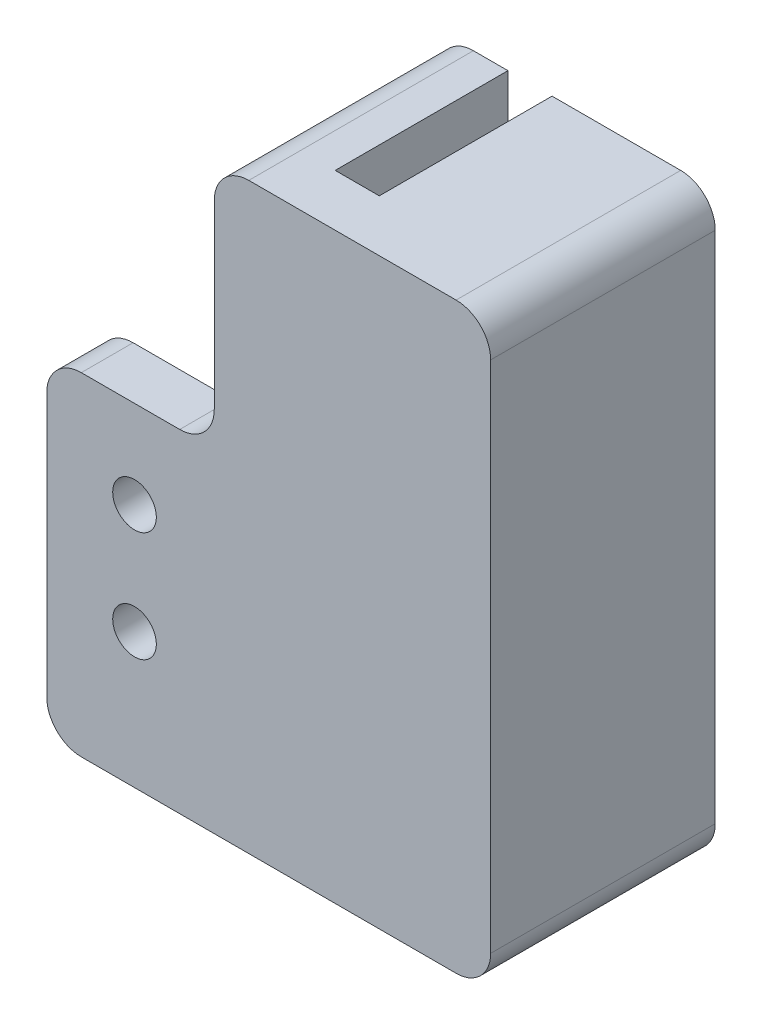
SolidWorks part; units mm, degrees
ref_plane "Front Plane" through (0, 0, 0) normal (0, 0, 1) x (1, 0, 0)
ref_plane "Top Plane" through (0, 0, 0) normal (0, 1, 0) x (1, 0, 0)
ref_plane "Right Plane" through (0, 0, 0) normal (1, 0, 0) x (0, 0, -1)
sketch "Sketch1" plane through (0, 0, 0) normal (0, 0, 1) x (1, 0, 0)
  line L16 (520, -4) -> (520, -16)
  line L17 (524, -20) -> (548, -20)
  line L18 (552, -16) -> (552, 96)
  line L19 (548, 100) -> (524, 100)
  line L20 (520, 96) -> (520, 42.5262)
  line L21 (516, 38.5262) -> (504.6076, 38.5262)
  line L22 (500.6076, 34.5262) -> (500.6076, 24)
  line L23 (496.6076, 20) -> (55.3924, 20)
  line L24 (51.3924, 24) -> (51.3924, 34.5262)
  line L25 (47.3924, 38.5262) -> (36, 38.5262)
  line L26 (32, 42.5262) -> (32, 96)
  line L27 (28, 100) -> (4, 100)
  line L28 (0, 96) -> (0, -16)
  line L29 (4, -20) -> (28, -20)
  line L30 (32, -16) -> (32, -4)
  line L31 (36, 0) -> (516, 0)
  line L32 (520, -4) -> (520, -16)
  line L33 (524, -20) -> (548, -20)
  line L34 (552, -16) -> (552, 96)
  line L35 (548, 100) -> (524, 100)
  line L36 (520, 96) -> (520, 42.5262)
  line L37 (516, 38.5262) -> (504.6076, 38.5262)
  line L38 (500.6076, 34.5262) -> (500.6076, 24)
  line L39 (496.6076, 20) -> (55.3924, 20)
  line L40 (51.3924, 24) -> (51.3924, 34.5262)
  line L41 (47.3924, 38.5262) -> (36, 38.5262)
  line L42 (32, 42.5262) -> (32, 96)
  line L43 (28, 100) -> (4, 100)
  line L44 (0, 96) -> (0, -16)
  line L45 (4, -20) -> (28, -20)
  line L46 (32, -16) -> (32, -4)
  line L47 (36, 0) -> (516, 0)
  circle A0 centre (510.7676, 15.6362) radius 2.525 construction
  circle A1 centre (510.7676, 28.3662) radius 2.525 construction
  circle A2 centre (548.5, 22.5) radius 1.7 construction
  circle A3 centre (523.5, 22.5) radius 1.7 construction
  circle A4 centre (523.5, 57.5) radius 1.7 construction
  circle A5 centre (548.5, 57.5) radius 1.7 construction
  circle A6 centre (510.7676, 15.6362) radius 2.525
  circle A7 centre (510.7676, 28.3662) radius 2.525
  circle A8 centre (548.5, 22.5) radius 1.7
  circle A9 centre (523.5, 22.5) radius 1.7
  circle A10 centre (523.5, 57.5) radius 1.7
  circle A11 centre (548.5, 57.5) radius 1.7
  arc A28 (520, -16) -> (524, -20) centre (524, -16) ccw
  arc A29 (548, -20) -> (552, -16) centre (548, -16) ccw
  arc A30 (552, 96) -> (548, 100) centre (548, 96) ccw
  arc A31 (524, 100) -> (520, 96) centre (524, 96) ccw
  arc A32 (516, 38.5262) -> (520, 42.5262) centre (516, 42.5262) ccw
  arc A33 (504.6076, 38.5262) -> (500.6076, 34.5262) centre (504.6076, 34.5262) ccw
  arc A34 (496.6076, 20) -> (500.6076, 24) centre (496.6076, 24) ccw
  arc A35 (51.3924, 24) -> (55.3924, 20) centre (55.3924, 24) ccw
  arc A36 (51.3924, 34.5262) -> (47.3924, 38.5262) centre (47.3924, 34.5262) ccw
  arc A37 (32, 42.5262) -> (36, 38.5262) centre (36, 42.5262) ccw
  arc A38 (32, 96) -> (28, 100) centre (28, 96) ccw
  arc A39 (4, 100) -> (0, 96) centre (4, 96) ccw
  arc A40 (0, -16) -> (4, -20) centre (4, -16) ccw
  arc A41 (28, -20) -> (32, -16) centre (28, -16) ccw
  arc A42 (36, 0) -> (32, -4) centre (36, -4) ccw
  arc A43 (520, -4) -> (516, 0) centre (516, -4) ccw
  arc A44 (520, -16) -> (524, -20) centre (524, -16) ccw
  arc A45 (548, -20) -> (552, -16) centre (548, -16) ccw
  arc A46 (552, 96) -> (548, 100) centre (548, 96) ccw
  arc A47 (524, 100) -> (520, 96) centre (524, 96) ccw
  arc A48 (516, 38.5262) -> (520, 42.5262) centre (516, 42.5262) ccw
  arc A49 (504.6076, 38.5262) -> (500.6076, 34.5262) centre (504.6076, 34.5262) ccw
  arc A50 (496.6076, 20) -> (500.6076, 24) centre (496.6076, 24) ccw
  arc A51 (51.3924, 24) -> (55.3924, 20) centre (55.3924, 24) ccw
  arc A52 (51.3924, 34.5262) -> (47.3924, 38.5262) centre (47.3924, 34.5262) ccw
  arc A53 (32, 42.5262) -> (36, 38.5262) centre (36, 42.5262) ccw
  arc A54 (32, 96) -> (28, 100) centre (28, 96) ccw
  arc A55 (4, 100) -> (0, 96) centre (4, 96) ccw
  arc A56 (0, -16) -> (4, -20) centre (4, -16) ccw
  arc A57 (28, -20) -> (32, -16) centre (28, -16) ccw
  arc A58 (36, 0) -> (32, -4) centre (36, -4) ccw
  arc A59 (520, -4) -> (516, 0) centre (516, -4) ccw
  dimension "D1" = 0
sketch "Sketch2" plane through (0, 0, 0) normal (0, 0, 1) x (1, 0, 0)
  circle A0 centre (510.7676, 15.6362) radius 2.525 construction
  circle A1 centre (510.7676, 28.3662) radius 2.525 construction
  circle A2 centre (548.5, 22.5) radius 1.7 construction
  circle A3 centre (523.5, 22.5) radius 1.7 construction
  circle A4 centre (548.5, 57.5) radius 1.7 construction
  circle A5 centre (523.5, 57.5) radius 1.7 construction
  circle A6 centre (510.7676, 15.6362) radius 2.525
  circle A7 centre (510.7676, 28.3662) radius 2.525
  circle A8 centre (548.5, 22.5) radius 1.7
  circle A9 centre (523.5, 22.5) radius 1.7
  circle A10 centre (548.5, 57.5) radius 1.7
  circle A11 centre (523.5, 57.5) radius 1.7
  circle A12 centre (496, 10) radius 1.7 construction
  circle A13 centre (496, 10) radius 1.7
sketch "Sketch3" plane through (0, 0, 0) normal (0, 0, 1) x (1, 0, 0)
  line L0 (516, 38.5262) -> (504.6076, 38.5262) construction
  line L1 (500.6076, 34.5262) -> (500.6076, 24) construction
  line L2 (516, 38.5262) -> (504.6076, 38.5262)
  line L3 (500.6076, 34.5262) -> (500.6076, 24)
  line L4 (552, -16) -> (552, 96) construction
  line L5 (36, 0) -> (516, 0) construction
  line L7 (552, 0) -> (552, 38.5262)
  line L8 (500.6076, 0) -> (516, 0)
  line L12 (516, 0) -> (552, 0)
  line L13 (520, 96) -> (520, 42.5262) construction
  line L14 (520, 67.5) -> (520, 42.5262)
  line L15 (520, 67.5) -> (552, 67.5)
  line L16 (552, 67.5) -> (552, 38.5262)
  line L17 (500.6076, 24) -> (500.6076, 0)
  arc A1 (504.6076, 38.5262) -> (500.6076, 34.5262) centre (504.6076, 34.5262) ccw construction
  arc A2 (504.6076, 38.5262) -> (500.6076, 34.5262) centre (504.6076, 34.5262) ccw
  arc A5 (516, 38.5262) -> (520, 42.5262) centre (516, 42.5262) ccw construction
  arc A6 (516, 38.5262) -> (520, 42.5262) centre (516, 42.5262) ccw
  circle A7 centre (523.5, 57.5) radius 1.7 construction
  dimension "D2" = 10
extrude "Boss-Extrude1" add sketch "Sketch3" along normal blind 26
sketch "Sketch4" plane through (0, 0, 0) normal (0, 0, -1) x (-1, 0, 0)
  line L0 (-500.6076, 0) -> (-552, 0) construction
  line L1 (-533.1076, 67.5) -> (-500.6076, 67.5)
  line L2 (-533.1076, 67.5) -> (-533.1076, 0)
  line L3 (-533.1076, 0) -> (-500.6076, 0)
  line L4 (-500.6076, 67.5) -> (-500.6076, 0)
  line L5 (-500.6076, 34.5262) -> (-500.6076, 0) construction
  line L7 (-552, 67.5) -> (-520, 67.5) construction
  point P4 (502.5202, 0)
  point P9 (528.4486, 67.5)
  point P10 (-531.1095, 67.5)
  dimension "D1" = 32.5
extrude "Cut-Extrude1" cut sketch "Sketch4" against normal blind 20
sketch "Sketch5" plane through (0, 0, 20) normal (0, 0, -1) x (-1, 0, 0)
  circle A0 centre (-510.7676, 28.3662) radius 2.525 construction
  circle A1 centre (-510.7676, 15.6362) radius 2.525 construction
  circle A2 centre (-510.7676, 28.3662) radius 2.525
  circle A3 centre (-510.7676, 15.6362) radius 2.525
extrude "Cut-Extrude2" cut sketch "Sketch5" against normal through all
sketch "Sketch6" plane through (0, 0, 20) normal (0, 0, -1) x (-1, 0, 0)
  line L0 (-533.1076, 0) -> (-500.6076, 0) construction
  line L1 (-520, 67.5) -> (-528, 67.5)
  line L2 (-520, 67.5) -> (-520, 0)
  line L3 (-520, 0) -> (-528, 0)
  line L4 (-528, 67.5) -> (-528, 0)
  dimension "D1" = 8
extrude "Boss-Extrude2" add sketch "Sketch6" along normal blind 20
sketch "Sketch7" plane through (0, 0, 0) normal (0, 0, -1) x (-1, 0, 0)
  circle A0 centre (-523.5, 5) radius 1.7 construction
  circle A1 centre (-548.5, 5) radius 1.7 construction
  circle A2 centre (-523.5, 5) radius 1.7
  circle A3 centre (-548.5, 5) radius 1.7
fillet "Fillet3" radius 4 5 edges at (552, 67.5, 13) (520, 67.5, 13) (552, 0, 13) (520, 0, 10) (500.6076, 0, 23)
sketch "Sketch9" plane through (0, 0, 0) normal (0, 0, -1) x (-1, 0, 0)
  circle A0 centre (-523.5, 5) radius 3.25
  circle A1 centre (-548.5, 5) radius 3.25
  dimension "D1" = 6.5
extrude "Cut-Extrude3" cut sketch "Sketch9" against normal blind 5
hole_wizard "M3x0.5 Tapped Hole1" positions "Sketch10" profile "Sketch12" tap size "M3x0.5" standard "ANSI Metric"
sketch "Sketch10" plane through (0, 0, 0) normal (0, 0, -1) x (-1, 0, 0)
  point P0 (-523.5, 57.5)
  point P3 (-548.5, 57.5)
  point P6 (-548.5, 22.5)
  point P9 (-523.5, 22.5)
sketch "Sketch12" plane through (523.5, 57.5, 0) normal (1, 0, 0) x (0, 1, 0)
  line L0 (0, 0) -> (0, 10.7511)
  line L1 (0, 10.7511) -> (1.25, 10)
  line L2 (1.25, 10) -> (1.25, 0.275)
  line L3 (1.25, 0.275) -> (1.525, 0)
  line L5 (1.525, 0) -> (0, 0)
  line L6 (-1.25, 0.275) -> (-1.525, 0) construction
  line L10 (0, 10.7511) -> (-1.25, 10) construction
  line L11 (0, -6.35) -> (0, 107.95) construction
  dimension "Tap Drill Dia." = 2.5
  dimension "Tap Drill Depth" = 10
  dimension "Near C'Sink Dia." = 3.05
  dimension "Near C'Sink Angle" = 90
  dimension "Drill Angle" = 118
cosmetic thread "Hole Thread1" parameters "D1"=6, "D2"=3
cosmetic thread "Hole Thread2" parameters "D1"=6, "D2"=3
cosmetic thread "Hole Thread3" parameters "D1"=6, "D2"=3
cosmetic thread "Hole Thread4" parameters "D1"=6, "D2"=3
